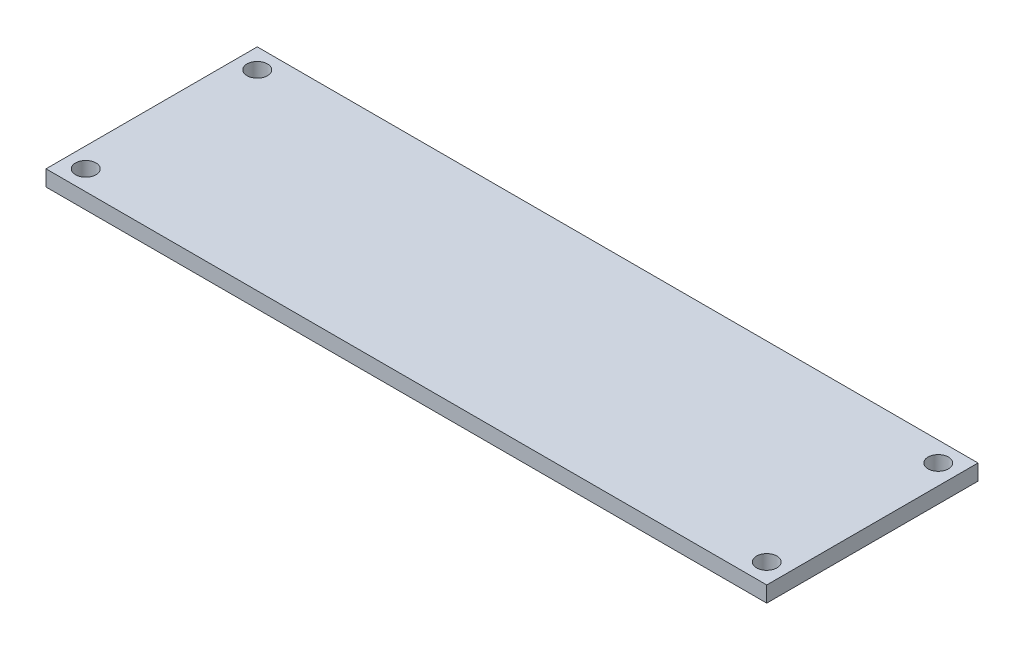
SolidWorks part; units mm, degrees
ref_plane "Front Plane" through (0, 0, 0) normal (0, 0, 1) x (1, 0, 0)
ref_plane "Top Plane" through (0, 0, 0) normal (0, 1, 0) x (1, 0, 0)
ref_plane "Right Plane" through (0, 0, 0) normal (1, 0, 0) x (0, 0, -1)
ref_plane "Plane1" through (0, -0.635, 0) normal (0, -1, 0) x (1, 0, 0)
sketch "Sketch1" plane through (0, -0.635, 0) normal (0, -1, 0) x (1, 0, 0)
  line L0 (-29, 8.5) -> (-29, -8.5)
  line L1 (-29, -8.5) -> (29, -8.5)
  line L2 (29, -8.5) -> (29, 8.5)
  line L3 (29, 8.5) -> (-29, 8.5)
  circle A0 centre (27.4, -6.9) radius 0.825
  circle A1 centre (27.4, 6.9) radius 0.825
  circle A2 centre (-27.4, -6.9) radius 0.825
  circle A3 centre (-27.4, 6.9) radius 0.825
extrude "Boss-Extrude1" add sketch "Sketch1" against normal blind 1.27
